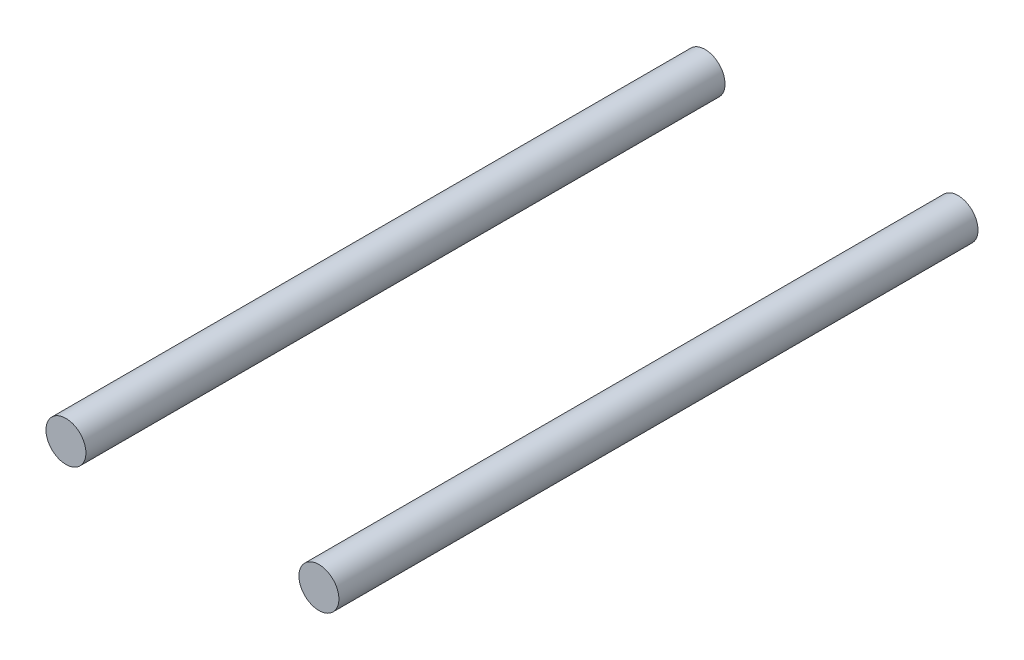
SolidWorks part; units mm, degrees
ref_plane "Front Plane" through (0, 0, 0) normal (0, 0, 1) x (1, 0, 0)
ref_plane "Top Plane" through (0, 0, 0) normal (0, 1, 0) x (1, 0, 0)
ref_plane "Right Plane" through (0, 0, 0) normal (1, 0, 0) x (0, 0, -1)
sketch "Sketch1" plane through (0, 0, 0) normal (0, 0, 1) x (1, 0, 0)
  line L0 (0, 0) -> (0, 16.6727) construction
  circle A0 centre (-9.5, 0) radius 1.5
  circle A1 centre (9.5, 0) radius 1.5
  dimension "D1" = 3
  dimension "D2" = 19
extrude "Boss-Extrude1" add sketch "Sketch1" along normal blind 19 and the other way blind 29 contours A0 | A1
